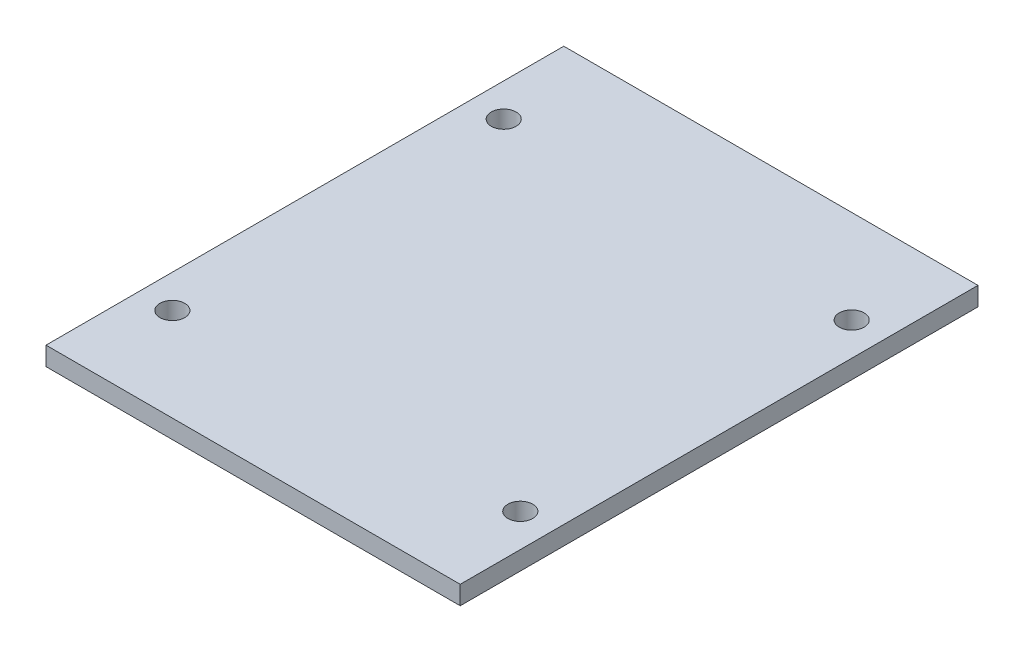
SolidWorks part; units mm, degrees
ref_plane "Front Plane" through (0, 0, 0) normal (0, 0, 1) x (1, 0, 0)
ref_plane "Top Plane" through (0, 0, 0) normal (0, 1, 0) x (1, 0, 0)
ref_plane "Right Plane" through (0, 0, 0) normal (1, 0, 0) x (0, 0, -1)
sketch "Sketch1" plane through (0, 0, 0) normal (0, 0, 1) x (1, 0, 0)
  line L1 (0, 0) -> (200, 0)
  line L2 (0, 0) -> (0, -9)
  line L3 (0, -9) -> (200, -9)
  line L4 (200, 0) -> (200, -9)
  dimension "D1" = 9
  dimension "D2" = 200
extrude "Boss-Extrude1" add sketch "Sketch1" along normal blind 250 contours L3 L4 L1 L2
sketch "Sketch2" plane through (0, 0, 0) normal (0, 1, 0) x (1, 0, 0)
  line L0 (200, -250) -> (200, 0) construction
  line L1 (0, -250) -> (0, 0) construction
  line L2 (0, 0) -> (200, 0) construction
  circle A0 centre (16, -45) radius 6
  circle A1 centre (184, -45) radius 6
  circle A2 centre (16, -205) radius 6
  circle A3 centre (184, -205) radius 6
  dimension "D1" = 12
  dimension "D2" = 12
  dimension "D3" = 12
  dimension "D4" = 12
  dimension "D5" = 160
  dimension "D6" = 16
  dimension "D7" = 16
  dimension "D8" = 45
extrude "Cut-Extrude2" cut sketch "Sketch2" against normal through all
equation "\"D7@Sketch2\"=\"D6@Sketch2\""
equation "\"D4@Sketch2\"=\"D3@Sketch2\""
equation "\"D2@Sketch2\"=\"D3@Sketch2\""
equation "\"D1@Sketch2\"=\"D3@Sketch2\""
